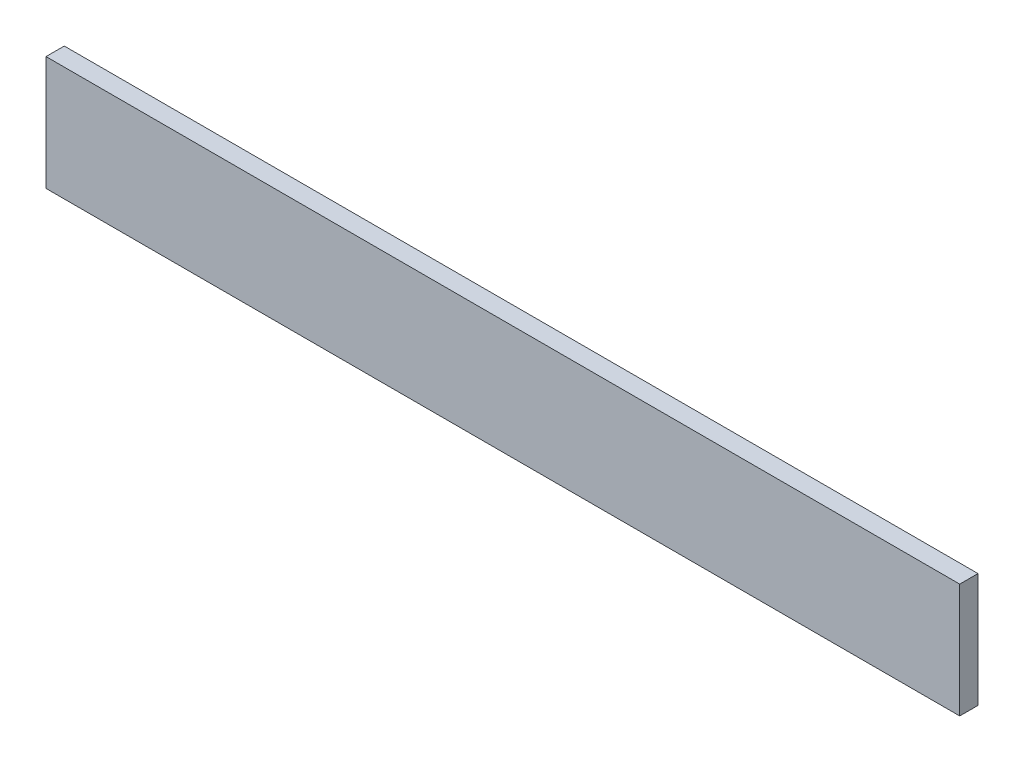
SolidWorks part; units mm, degrees
ref_plane "Front Plane" through (0, 0, 0) normal (0, 0, 1) x (1, 0, 0)
ref_plane "Top Plane" through (0, 0, 0) normal (0, 1, 0) x (1, 0, 0)
ref_plane "Right Plane" through (0, 0, 0) normal (1, 0, 0) x (0, 0, -1)
ref_plane "Plane1" through (0, 0, 10) normal (0, 0, 1) x (1, 0, 0)
sketch "Sketch2" plane through (0, -10, 10) normal (0, 0, -1) x (1, 0, 0)
  line L1 (0, -10) -> (160, -10)
  line L2 (0, -10) -> (0, 10)
  line L3 (0, 10) -> (160, 10)
  line L4 (160, -10) -> (160, 10)
  dimension "D1" = 20
  dimension "D2" = 160
extrude "Boss-Extrude1" add sketch "Sketch2" along normal blind 3.2
sketch "Sketch4" plane through (0, 0, 0) normal (0, 1, 0) x (1, 0, 0)
  line L0 (0, -10) -> (160, -10) construction
  line L1 (0, -6.8) -> (80, -6.8)
  line L2 (0, -6.8) -> (0, -10)
  line L3 (0, -10) -> (80, -10)
  line L4 (80, -6.8) -> (80, -10)
  line L5 (160, -6.8) -> (160, -10) construction
  dimension "D1" = 80
  dimension "D2" = 80
